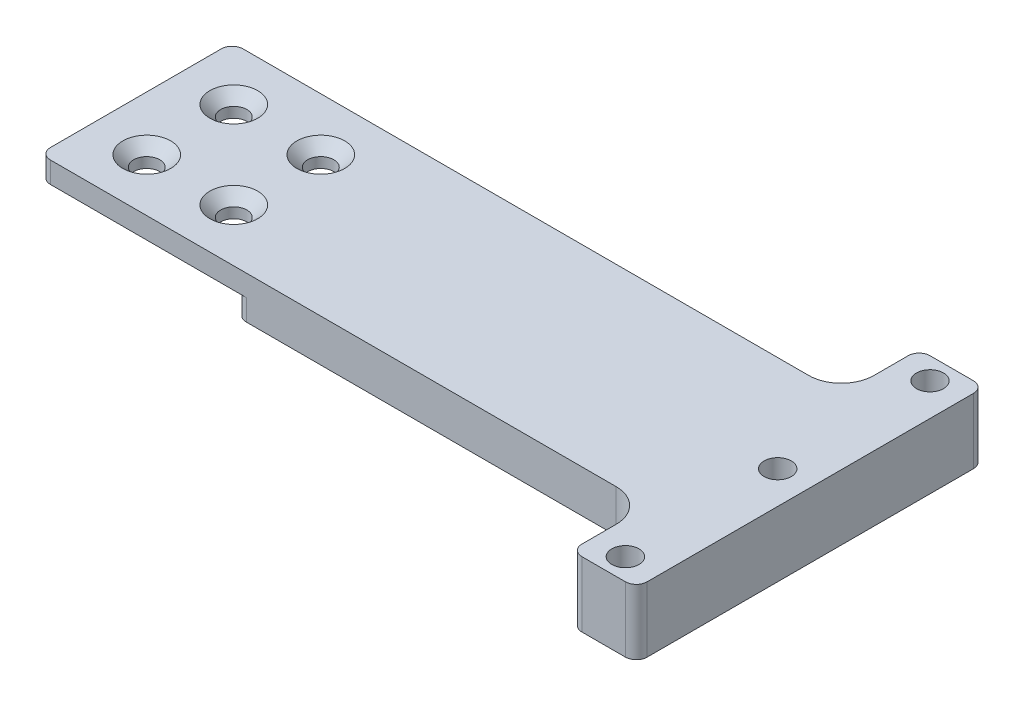
SolidWorks part; units mm, degrees
material "7075-T6, Plate (SS)"
ref_plane "Front Plane" through (0, 0, 0) normal (0, 0, 1) x (1, 0, 0)
ref_plane "Top Plane" through (0, 0, 0) normal (0, 1, 0) x (1, 0, 0)
ref_plane "Right Plane" through (0, 0, 0) normal (1, 0, 0) x (0, 0, -1)
sketch "Sketch1" plane through (0, 0, 0) normal (0, 1, 0) x (1, 0, 0)
  line L0 (0, 33.1008) -> (0, -39.9111) construction
  line L5 (-41.1596, 0) -> (51.6494, 0) construction
  line L6 (-31, 0) -> (-31, 11.9) construction
  line L7 (-31, 11.9) -> (22, 11.9) construction
  line L8 (22, 11.9) -> (25, 11.9)
  line L9 (28, 16) -> (31, 16) construction
  line L10 (31, 16) -> (31, 0) construction
  line L11 (25, 11.9) -> (25, 16) construction
  line L12 (25, 16) -> (28, 16) construction
  line L13 (-31, -11.9) -> (-31, 11.9)
  line L14 (-31, 11.9) -> (22, 11.9)
  line L15 (-31, -11.9) -> (22, -11.9)
  line L16 (25, 11.9) -> (25, 16)
  line L17 (25, -11.9) -> (25, -16)
  line L18 (25, 16) -> (28, 16)
  line L19 (25, -16) -> (28, -16)
  line L20 (28, 16) -> (31, 16)
  line L21 (28, -16) -> (31, -16)
  line L22 (31, 16) -> (31, -16)
  line L23 (25, -11.9) -> (22, -11.9)
  arc A1 (22, 11.9) -> (25, 11.9) centre (23.5, 11.9) ccw construction
  arc A2 (22, 11.9) -> (25, 11.9) centre (23.5, 11.9) ccw construction
  arc A3 (22, -11.9) -> (25, -11.9) centre (23.5, -11.9) cw construction
  dimension "D6" = 3
  dimension "D1" = 11.9
  dimension "D2" = 56
  dimension "D3" = 6
  dimension "D4" = 3
  dimension "D5" = 16
  dimension "D7" = 16
extrude "Boss-Extrude1" add sketch "Sketch1" along normal blind 3.9
sketch "Sketch6" plane through (0, 0, 0) normal (0, -1, 0) x (1, 0, 0)
  line L0 (-8.2213, 0) -> (23.1303, 0) construction
  line L1 (25, 11.9) -> (25, 16)
  line L2 (25, -11.9) -> (25, -16)
  line L3 (25, 16) -> (28, 16)
  line L4 (25, -16) -> (28, -16)
  line L5 (28, 16) -> (31, 16)
  line L6 (28, -16) -> (31, -16)
  line L7 (31, 16) -> (31, -16)
  line L8 (25, 11.9) -> (25, -11.9)
  point P15 (31, 0)
  point P16 (25, 0)
extrude "Boss-Extrude2" add sketch "Sketch6" along normal blind 2.1
sketch "Sketch7" plane through (0, 3.9, 0) normal (0, 1, 0) x (1, 0, 0)
  line L0 (0, 0) -> (-36.1292, 0) construction
  line L1 (-31, 35.6068) -> (-31, -35.6068) construction
  line L2 (-31, 11.9) -> (-43.7821, 11.9) construction
  line L3 (22, 11.9) -> (22, -12.1) construction
  line L4 (-22, -32.0384) -> (-22, 31.8384) construction
  line L5 (-31, 9) -> (-23, 9)
  line L6 (-31, -9) -> (-23, -9)
  line L7 (-23, 9) -> (-23, 15)
  line L8 (-23, -9) -> (-23, -15)
  line L9 (-23, 15) -> (-31, 15)
  line L10 (-23, -15) -> (-31, -15)
  line L11 (-31, 15) -> (-31, 9)
  line L12 (-31, -15) -> (-31, -9)
  point P8 (-31, 0)
  point P14 (-22, 4)
  point P20 (-22, 0)
  dimension "D1" = 44
  dimension "D2" = 4
  dimension "D3" = 18
  dimension "D4" = 8
  dimension "D5" = 30
hole_wizard "CSK for M2 Countersunk Flat Head Screw1" positions "Sketch8" profile "Sketch9" countersink size "M2" standard "DIN" end condition through all
sketch "Sketch8" plane through (0, 3.9, 0) normal (0, 1, 0) x (1, 0, 0)
  line L0 (-31, 11.9) -> (-31, -11.9) construction
  line L1 (25, 11.9) -> (-31, 11.9) construction
  point P0 (-18, 4)
  dimension "D1" = 13
  dimension "D2" = 7.9
sketch "Sketch9" plane through (-18, 3.9, -4) normal (1, 0, 0) x (0, 0, 1)
  line L0 (0, 0) -> (0, 6)
  line L1 (0, 6) -> (1.2, 6)
  line L2 (1.2, 6) -> (1.2, 1)
  line L3 (1.2, 1) -> (2.2, 0)
  line L5 (2.2, 0) -> (0, 0)
  line L6 (-1.2, 1) -> (-2.2, 0) construction
  line L11 (0, -6.35) -> (0, 107.95) construction
  dimension "Thru Hole Dia." = 2.4
  dimension "Thru Hole Depth" = 6
  dimension "Near C'Sink Dia." = 4.4
  dimension "Near C'Sink Angle" = 90
pattern_linear "LPattern1" count 2 spacing 8 along (-1, 0, 0) count 2 spacing 8 along (0, 0, 1) of "CSK for M2 Countersunk Flat Head Screw1"
extrude "Cut-Extrude1" cut sketch "Sketch7" against normal through all
sketch "Sketch10" plane through (0, 0, 0) normal (0, -1, 0) x (1, 0, 0)
  line L0 (-31, 17.7226) -> (-31, -27.2243) construction
  line L1 (-31, 9) -> (-23, 9) construction
  line L2 (-22, 25.3555) -> (-22, -37.1384) construction
  line L3 (-31, -9) -> (-23, -9) construction
  line L6 (-31, 9) -> (-13, 9)
  line L7 (-31, 9) -> (-31, -9)
  line L8 (-31, -9) -> (-13, -9)
  line L9 (-13, 9) -> (-13, -9)
  dimension "D1" = 18
extrude "Cut-Extrude2" cut sketch "Sketch10" against normal blind 1.95
sketch "Sketch14" plane through (0, 1.95, 0) normal (0, -1, 0) x (1, 0, 0)
  line L0 (-31, -9.95) -> (-31, -8.95)
  line L1 (-31, 9) -> (-31, -9) construction
  line L2 (-31, -8.95) -> (-23, -8.95)
  line L3 (-23, -8.95) -> (-23, -9.95)
  line L4 (-23, -9.95) -> (-31, -9.95)
  line L5 (-31, 8.95) -> (-31, 9.95)
  line L6 (-31, 9.95) -> (-23, 9.95)
  line L7 (-23, 9.95) -> (-23, 8.95)
  line L8 (-23, 8.95) -> (-31, 8.95)
  line L9 (-23, 11.9) -> (-23, 9) construction
  line L10 (-31, -9) -> (-23, -9) construction
  dimension "D1" = 17.9
  dimension "D2" = 0.05
  dimension "D3" = 1
extrude "Cut-Extrude3" cut sketch "Sketch14" against normal through all
sketch "Sketch11" plane through (0, 3.9, 0) normal (0, 1, 0) x (1, 0, 0)
  line L0 (28, 30.2233) -> (28, -32.141) construction
  line L1 (31, 16) -> (31, -16) construction
  line L4 (25, 16) -> (28, 16) construction
  line L5 (-200041.1596, 0) -> (200051.6494, 0) construction
  line L6 (-3.3, 0) -> (3.3, 0) construction
  point P5 (28, 14)
  point P8 (28, 5)
  point P13 (28, -5)
  point P14 (28, -14)
  dimension "D1" = 3
  dimension "D2" = 2
  dimension "D3" = 5
hole_wizard "M3 Tapped Hole1" positions "Sketch12" profile "Sketch13" tap size "M3" standard "KS"
sketch "Sketch12" plane through (0, 3.9, 0) normal (0, 1, 0) x (1, 0, 0)
  line L1 (0, 0) -> (28, 0) construction
  point P0 (28, 14)
  point P3 (28, -14)
  point P15 (28, 0)
sketch "Sketch13" plane through (28, 3.9, -14) normal (1, 0, 0) x (0, 0, 1)
  line L0 (0, 0) -> (0, 7.5)
  line L1 (0, 7.5) -> (1.25, 6.7489)
  line L2 (1.25, 6.7489) -> (1.25, 0)
  line L5 (1.25, 0) -> (0, 0)
  line L10 (0, 7.5) -> (-1.25, 6.7489) construction
  line L11 (0, -6.35) -> (0, 107.95) construction
  dimension "Tap Drill Dia." = 2.5
  dimension "Tap Drill Depth" = 7.5
  dimension "Drill Angle" = 118
cosmetic thread "Cosmetic Thread1" parameters "D2"=3
cosmetic thread "Cosmetic Thread2" parameters "D2"=3
cosmetic thread "Cosmetic Thread3" parameters "D2"=3
sketch "Sketch15" plane through (0, 3.9, 0) normal (0, 1, 0) x (1, 0, 0)
  line L0 (-23, -11.9) -> (25, -11.9) construction
  line L1 (-31, 8.85) -> (25, 8.85)
  line L2 (-31, 8.85) -> (-31, 11.9)
  line L3 (-31, 11.9) -> (25, 11.9)
  line L4 (25, 8.85) -> (25, 11.9)
  line L5 (-31, -8.85) -> (25, -8.85)
  line L6 (-31, -8.85) -> (-31, -11.9)
  line L7 (-31, -11.9) -> (25, -11.9)
  line L8 (25, -8.85) -> (25, -11.9)
  line L9 (25, 11.9) -> (-23, 11.9) construction
  line L10 (25, 16) -> (25, 11.9) construction
  line L11 (-31, 8.95) -> (-31, -8.95) construction
  point P21 (-31, 10.375)
  dimension "D1" = 3.05
  dimension "D2" = 3.05
extrude "Cut-Extrude4" cut sketch "Sketch15" against normal through all
fillet "Fillet5" radius 1 8 edges at (25, 0.9, -16) (31, 0.9, -16) (31, 0.9, 16) (25, 0.9, 16) (-31, 2.925, 8.85) (-31, 2.925, -8.85) (-13, 0.975, 8.85) (-13, 0.975, -8.85)
fillet "Fillet7" radius 3 2 edges at (25, 1.95, 8.85) (25, 1.95, -8.85)
